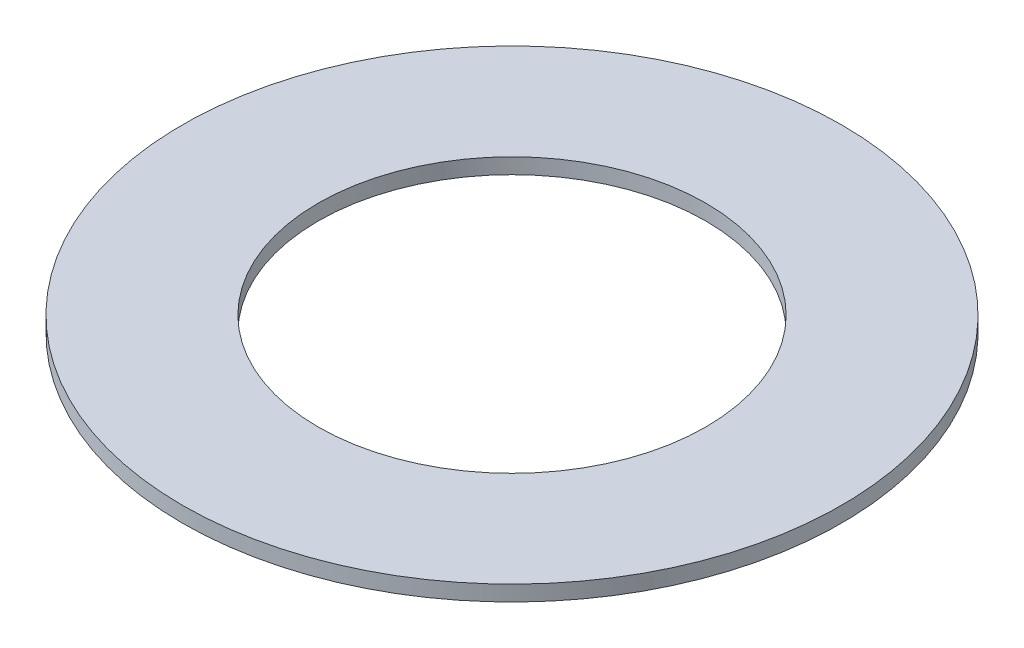
SolidWorks part; units mm, degrees
ref_plane "Front Plane" through (0, 0, 0) normal (0, 0, 1) x (1, 0, 0)
ref_plane "Top Plane" through (0, 0, 0) normal (0, 1, 0) x (1, 0, 0)
ref_plane "Right Plane" through (0, 0, 0) normal (1, 0, 0) x (0, 0, -1)
sketch "Sketch1" plane through (0, 0, 0) normal (0, 1, 0) x (1, 0, 0)
  circle A0 centre (0, 0) radius 6.35
  circle A1 centre (0, 0) radius 10.795
  dimension "D1" = 12.7
  dimension "D2" = 21.59
extrude "Boss-Extrude1" add sketch "Sketch1" along normal blind 0.508 contours A1
sketch "Sketch2" plane through (0, 0.508, 0) normal (0, 1, 0) x (1, 0, 0)
  circle A0 centre (0, 0) radius 6.35
  dimension "D1" = 12.7
extrude "Cut-Extrude1" cut sketch "Sketch2" against normal through all
